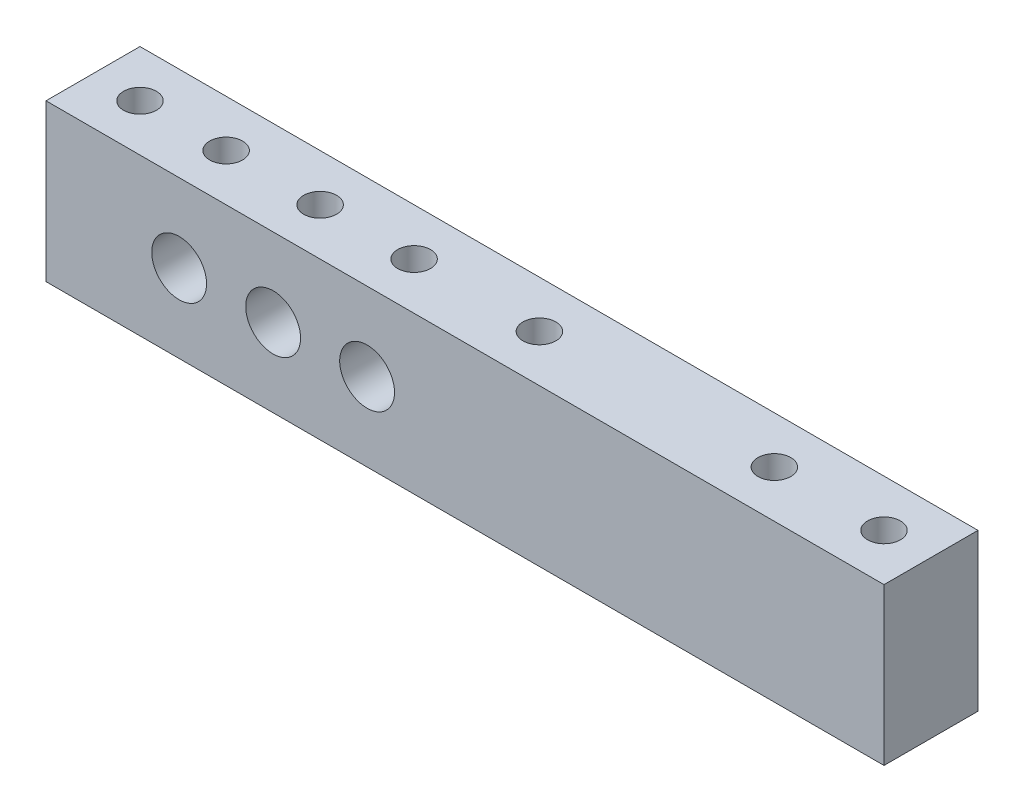
SolidWorks part; units mm, degrees
ref_plane "Ebene vorne" through (0, 0, 0) normal (0, 0, 1) x (1, 0, 0)
ref_plane "Ebene oben" through (0, 0, 0) normal (0, 1, 0) x (1, 0, 0)
ref_plane "Ebene rechts" through (0, 0, 0) normal (1, 0, 0) x (0, 0, -1)
sketch "Skizze1" plane through (0, 0, 0) normal (0, 0, 1) x (1, 0, 0)
  line L1 (0, 0) -> (107, 0)
  line L2 (0, 0) -> (0, 20)
  line L3 (0, 20) -> (107, 20)
  line L4 (107, 0) -> (107, 20)
  dimension "D1" = 107
  dimension "D2" = 20
extrude "Aufsatz-Linear austragen1" add sketch "Skizze1" along normal blind 12
hole_wizard "Ø7.0 (7) Durchmesser Bohrung1" positions "Skizze2" profile "Skizze3" hole size "Ø7.0" standard "DIN" end condition up to next
sketch "Skizze2" plane through (0, 0, 12) normal (0, 0, 1) x (1, 0, 0)
  line L0 (0, 20) -> (0, 0) construction
  line L1 (107, 20) -> (0, 20) construction
  point P0 (17, 10)
  point P2 (29, 10)
  point P4 (41, 10)
  point P9 (0, 0)
  point P10 (0, 0)
  dimension "D1" = 17
  dimension "D2" = 12
  dimension "D3" = 12
  dimension "D4" = 10
  dimension "D5" = 10
  dimension "D6" = 10
sketch "Skizze3" plane through (17, 10, 12) normal (1, 0, 0) x (0, -1, 0)
  line L0 (0, 0) -> (0, 12)
  line L1 (0, 12) -> (3.5, 12)
  line L2 (3.5, 12) -> (3.5, 0)
  line L5 (3.5, 0) -> (0, 0)
  line L11 (0, -6.35) -> (0, 107.95) construction
  dimension "Bohrerdurchmesser" = 7
  dimension "Bohrungstiefe" = 12
hole_wizard "M5 Gewindebohrung1" positions "Skizze7" profile "Skizze8" tap size "M5" standard "ISO" end condition up to next
sketch "Skizze7" plane through (0, 20, 0) normal (0, 1, 0) x (1, 0, 0)
  line L0 (107, 0) -> (0, 0) construction
  line L1 (0, -12) -> (0, 0) construction
  line L2 (107, -12) -> (107, 0) construction
  point P0 (6, -6)
  point P2 (101, -6)
  point P4 (87, -6)
  point P6 (57, -6)
  point P11 (0, 0)
  dimension "D1" = 6
  dimension "D2" = 6
  dimension "D3" = 6
  dimension "D4" = 6
  dimension "D5" = 6
  dimension "D6" = 6
  dimension "D7" = 20
  dimension "D8" = 30
sketch "Skizze8" plane through (6, 20, 6) normal (1, 0, 0) x (0, 0, 1)
  line L0 (0, 0) -> (0, 20)
  line L1 (0, 20) -> (2.1, 20)
  line L2 (2.1, 20) -> (2.1, 0)
  line L5 (2.1, 0) -> (0, 0)
  line L11 (0, -6.35) -> (0, 107.95) construction
  dimension "Bohrerdurchmesser" = 4.2
  dimension "Bohrungstiefe" = 20
cosmetic thread "Bohrungsgewinde1" parameters "D2"=5
cosmetic thread "Bohrungsgewinde2" parameters "D2"=5
cosmetic thread "Bohrungsgewinde3" parameters "D2"=5
cosmetic thread "Bohrungsgewinde4" parameters "D2"=5
hole_wizard "M5 Gewindebohrung2" positions "Skizze9" profile "Skizze10" tap size "M5" standard "ISO"
sketch "Skizze9" plane through (0, 20, 0) normal (0, 1, 0) x (1, 0, 0)
  line L0 (107, 0) -> (0, 0) construction
  line L1 (0, -12) -> (0, 0) construction
  point P0 (17, -6)
  point P2 (29, -6)
  point P4 (41, -6)
  dimension "D1" = 6
  dimension "D2" = 6
  dimension "D3" = 6
  dimension "D4" = 17
  dimension "D5" = 12
  dimension "D6" = 12
sketch "Skizze10" plane through (17, 20, 6) normal (1, 0, 0) x (0, 0, 1)
  line L0 (0, 0) -> (0, 11.2618)
  line L1 (0, 11.2618) -> (2.1, 10)
  line L2 (2.1, 10) -> (2.1, 0)
  line L5 (2.1, 0) -> (0, 0)
  line L10 (0, 11.2618) -> (-2.1, 10) construction
  line L11 (0, -6.35) -> (0, 107.95) construction
  dimension "Bohrerdurchmesser" = 4.2
  dimension "Bohrungstiefe" = 10
  dimension "Spitzenwinkel" = 118
cosmetic thread "Bohrungsgewinde5" parameters "D1"=6, "D2"=5
cosmetic thread "Bohrungsgewinde6" parameters "D1"=6, "D2"=5
cosmetic thread "Bohrungsgewinde7" parameters "D1"=6, "D2"=5
